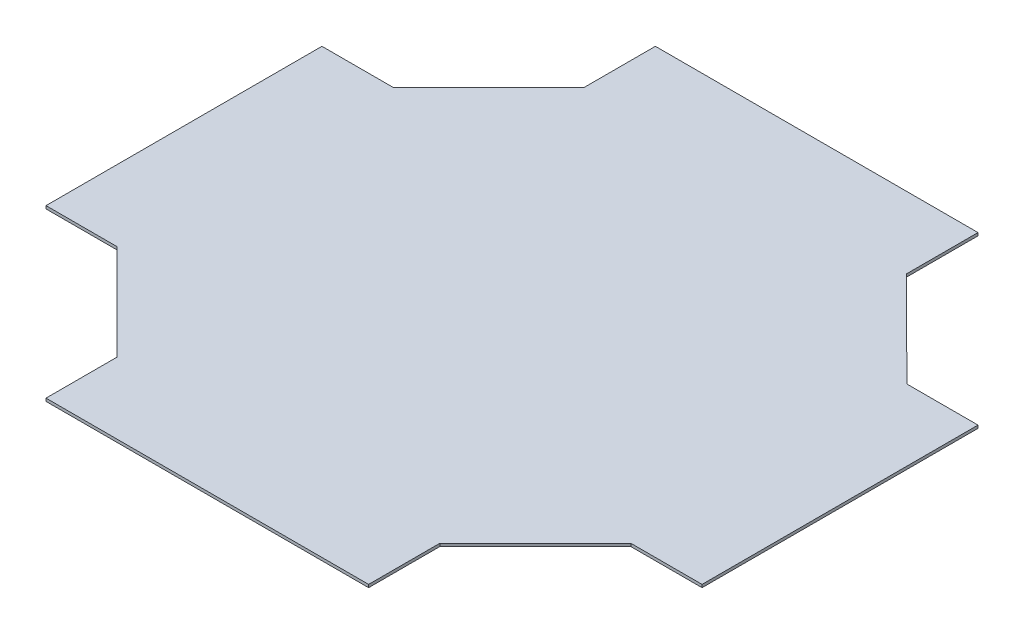
SolidWorks part; units mm, degrees
ref_plane "Front Plane" through (0, 0, 0) normal (0, 0, 1) x (1, 0, 0)
ref_plane "Top Plane" through (0, 0, 0) normal (0, 1, 0) x (1, 0, 0)
ref_plane "Right Plane" through (0, 0, 0) normal (1, 0, 0) x (0, 0, -1)
sketch "Sketch1" plane through (0, 0, 0) normal (0, 1, 0) x (1, 0, 0)
  line L0 (-245.2753, 194.8598) -> (-166.6798, 194.8598)
  line L1 (-166.6798, 194.8598) -> (-61.1253, 300.0523)
  line L2 (-61.1253, 379.0098) -> (-61.1253, 300.0523)
  line L3 (-61.1253, 379.0098) -> (295.2367, 379.0098)
  line L5 (-245.2753, -109.9402) -> (-166.6798, -109.9402)
  line L6 (-166.6798, -109.9402) -> (-61.1253, -215.4947)
  line L7 (-61.1253, -215.4947) -> (-61.1253, -294.0902)
  line L8 (-61.1253, -294.0902) -> (117.8177, -294.0902)
  line L9 (-245.2753, -109.9402) -> (-245.2753, 194.8598)
  line L10 (-245.2753, 194.8598) -> (-245.2753, -109.9402)
  line L11 (295.2367, -294.0902) -> (117.8177, -294.0902)
  line L12 (295.2367, -215.4947) -> (295.2367, -294.0902)
  line L13 (400.7912, -109.9402) -> (295.2367, -215.4947)
  line L14 (479.3867, -109.9402) -> (400.7912, -109.9402)
  line L15 (479.3867, 194.8598) -> (479.3867, -109.9402)
  line L16 (479.3867, 194.8598) -> (400.7912, 194.8598)
  line L17 (400.7912, 194.8598) -> (295.2367, 300.0523)
  line L18 (295.2367, 379.0098) -> (295.2367, 300.0523)
  line L19 (117.0557, 379.0098) -> (117.8177, -294.0902)
  line L20 (-166.6798, 194.8598) -> (-61.1253, 300.0523)
  line L21 (-61.1253, 379.0098) -> (117.0557, 379.0098)
  point P8 (0, 0)
  point P11 (117.8177, -294.3028)
extrude "Boss-Extrude1" add sketch "Sketch1" along normal blind 3.175 contours L19 L3 L2 L1 L0 L9 L5 L6 L7 L8 | L3 L19 L11 L12 L13 L14 L15 L16 L17 L18
